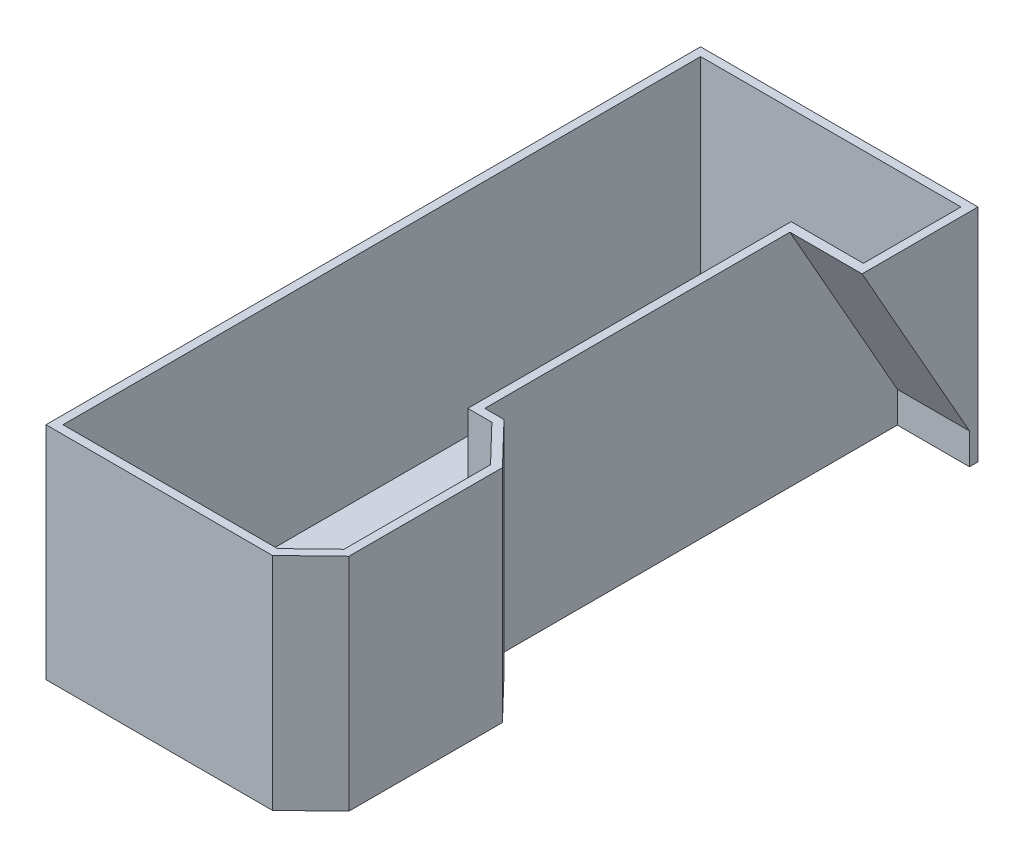
SolidWorks part; units mm, degrees
ref_plane "前视基准面" through (0, 0, 0) normal (0, 0, 1) x (1, 0, 0)
ref_plane "上视基准面" through (0, 0, 0) normal (0, 1, 0) x (1, 0, 0)
ref_plane "右视基准面" through (0, 0, 0) normal (1, 0, 0) x (0, 0, -1)
other "Configuration Table"
sketch "草图1" plane through (0, 0, 0) normal (0, 1, 0) x (1, 0, 0)
  line L1 (0, 0) -> (290, 0)
  line L2 (0, 0) -> (0, 925)
  line L3 (0, 925) -> (290, 925)
  line L4 (290, 0) -> (290, 925)
  dimension "D1" = 925
  dimension "D2" = 290
extrude "凸台-拉伸1" add sketch "草图1" along normal blind 12
sketch "草图3" plane through (0, 12, 0) normal (0, 1, 0) x (1, 0, 0)
  line L0 (290, 0) -> (290, 925) construction
  line L1 (290, 330) -> (317.1818, 330)
  line L2 (290, 330) -> (290, 0)
  line L3 (290, 0) -> (320, 0)
  line L4 (375, 270) -> (375, 53)
  line L5 (317.1818, 330) -> (375, 270)
  line L6 (375, 53) -> (320, 0)
  line L7 (0, 0) -> (290, 0) construction
  dimension "D1" = 330
  dimension "D2" = 0
  dimension "D3" = 30
  dimension "D4" = 85
  dimension "D5" = 60
  dimension "D6" = 217
extrude "凸台-拉伸3" add sketch "草图3" against normal blind 12
sketch "草图4" plane through (0, 12, 0) normal (0, 1, 0) x (1, 0, 0)
  line L16 (12, 913) -> (12, 12)
  line L17 (12, 12) -> (315.1591, 12)
  line L18 (315.1591, 12) -> (363, 58.1012)
  line L19 (363, 58.1012) -> (363, 265.1591)
  line L20 (363, 265.1591) -> (312.0806, 318)
  line L21 (312.0806, 318) -> (278, 318)
  line L22 (278, 318) -> (278, 913)
  line L23 (278, 913) -> (12, 913)
  line L24 (12, 913) -> (12, 12)
  line L25 (12, 12) -> (315.1591, 12)
  line L26 (315.1591, 12) -> (363, 58.1012)
  line L27 (363, 58.1012) -> (363, 265.1591)
  line L28 (363, 265.1591) -> (312.0806, 318)
  line L29 (312.0806, 318) -> (278, 318)
  line L30 (278, 318) -> (278, 913)
  line L31 (278, 913) -> (12, 913)
  line L40 (0, 925) -> (0, 0)
  line L41 (0, 0) -> (320, 0)
  line L42 (320, 0) -> (375, 53)
  line L43 (375, 53) -> (375, 270)
  line L44 (375, 270) -> (317.1818, 330)
  line L45 (317.1818, 330) -> (290, 330)
  line L46 (290, 330) -> (290, 925)
  line L47 (290, 925) -> (0, 925)
  line L48 (0, 925) -> (0, 0)
  line L49 (0, 0) -> (320, 0)
  line L50 (320, 0) -> (375, 53)
  line L51 (375, 53) -> (375, 270)
  line L52 (375, 270) -> (317.1818, 330)
  line L53 (317.1818, 330) -> (290, 330)
  line L54 (290, 330) -> (290, 925)
  line L55 (290, 925) -> (0, 925)
  dimension "D1" = 12
  dimension "D2" = 0
extrude "凸台-拉伸4" add sketch "草图4" along normal blind 300
sketch "草图5" plane through (290, 0, 0) normal (1, 0, 0) x (0, 0, -1)
  line L0 (775, 312) -> (925, 47)
  line L1 (330, 312) -> (925, 312) construction
  line L2 (925, 47) -> (925, 312)
  line L3 (925, 312) -> (775, 312)
  dimension "D1" = 150
  dimension "D2" = 265
extrude "切除-拉伸1" cut sketch "草图5" against normal blind 12
sketch "草图7" plane through (290, 0, 0) normal (1, 0, 0) x (0, 0, -1)
  line L0 (775, 312) -> (925, 47)
  line L1 (925, 47) -> (925, 22.6394)
  line L2 (925, 47) -> (925, 0) construction
  line L3 (925, 22.6394) -> (761.211, 312)
  line L4 (330, 312) -> (775, 312) construction
  line L5 (761.211, 312) -> (775, 312)
  dimension "D1" = 12
extrude "凸台-拉伸5" add sketch "草图7" along normal blind 90
sketch "草图8" plane through (278, 0, 0) normal (1, 0, 0) x (0, 0, -1)
  line L0 (925, 312) -> (925, 47)
  line L1 (925, 47) -> (913, 68.2)
  line L2 (775, 312) -> (925, 47) construction
  line L3 (913, 312) -> (913, 12) construction
  line L4 (913, 68.2) -> (913, 312)
  line L5 (913, 312) -> (925, 312)
extrude "凸台-拉伸6" add sketch "草图8" along normal blind 102
sketch "草图9" plane through (380, 0, 0) normal (1, 0, 0) x (0, 0, -1)
  line L0 (761.211, 312) -> (925, 312)
  line L1 (925, 312) -> (925, 22.6394)
  line L2 (925, 22.6394) -> (925, 312) construction
  line L3 (761.211, 312) -> (925, 22.6394) construction
  line L4 (925, 22.6394) -> (761.211, 312)
extrude "凸台-拉伸7" add sketch "草图9" along normal blind 12
sketch "草图10" plane through (290, 0, 0) normal (1, 0, 0) x (0, 0, -1)
  line L0 (925, 0) -> (925, 22.6394)
  line L1 (925, 22.6394) -> (913, 43.8394)
  line L2 (761.211, 312) -> (925, 22.6394) construction
  line L3 (913, 43.8394) -> (913, 0)
  line L4 (330, 0) -> (925, 0) construction
  line L5 (913, 0) -> (925, 0)
  dimension "D1" = 12
extrude "凸台-拉伸8" add sketch "草图10" along normal up to surface (102 mm away) up to face at (392, 215.5465, -870.4037)
equation "\"D2@草图1\"=220+70"
equation "\"D1@凸台-拉伸6\"=90+12"
